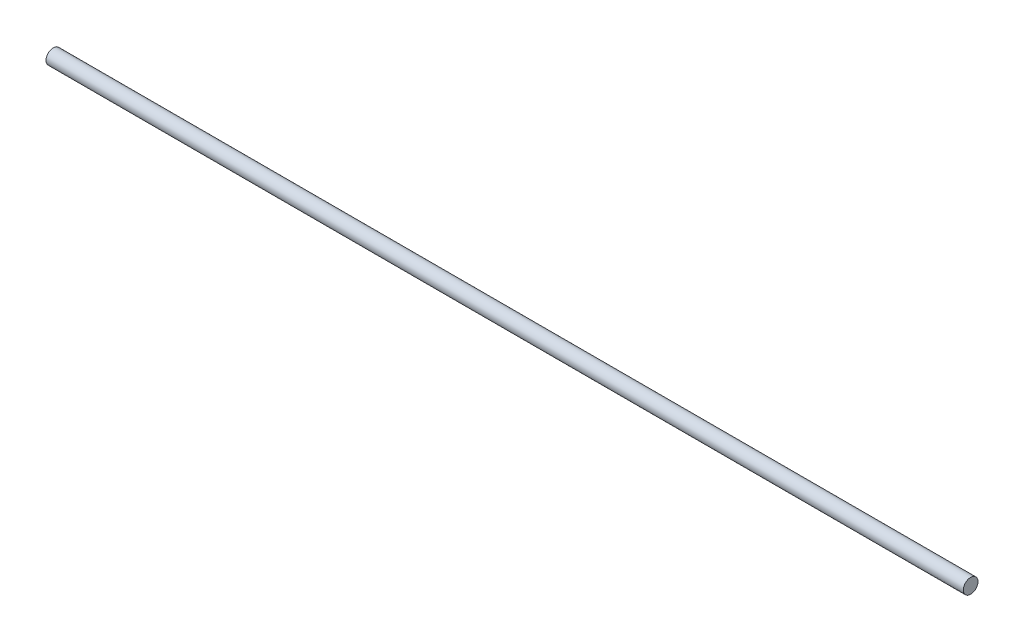
SolidWorks part; units mm, degrees
material "1023 Carbon Steel Sheet (SS)"
ref_plane "Front Plane" through (0, 0, 0) normal (0, 0, 1) x (1, 0, 0)
ref_plane "Top Plane" through (0, 0, 0) normal (0, 1, 0) x (1, 0, 0)
ref_plane "Right Plane" through (0, 0, 0) normal (1, 0, 0) x (0, 0, -1)
sketch "Sketch1" plane through (0, 0, 0) normal (1, 0, 0) x (0, 0, -1)
  circle A0 centre (0, 0) radius 6
  dimension "D1" = 12
extrude "Boss-Extrude1" add sketch "Sketch1" along normal blind 750
cosmetic thread "Cosmetic Thread1" parameters "D1"=750, "D2"=9.853
sketch "Sketch2" plane through (0, 0, 0) normal (0, 0, 1) x (1, 0, 0)
  line L0 (749.135, 6) -> (750.865, 6)
  line L1 (750.865, 6) -> (750, 4.9265)
  line L2 (750, -6) -> (750, 6) construction
  line L3 (750, 4.9265) -> (750, 6) construction
  line L4 (749.135, 6) -> (750, 4.9265)
  line L5 (750, 4.9265) -> (750, 0) construction
  dimension "D1" = 0.865
  dimension "D2" = 4.9265
sketch "Sketch4" plane through (750, 0, 0) normal (1, 0, 0) x (0, 0, -1)
  circle A0 centre (0, 0) radius 6
curve "Helix/Spiral1" pitch 1.75 height 750 turns 428.5714
equation "\"D1@Sketch2\"= \"ThreadPitch\" / 2 - 0.01 'Need to take off a fraction extra so the helix cut works"
equation "\"ThreadPitch\"= 1.75'M12 thread pitch"
equation "\"MinorThreadDiameter\"= 9.853'M12 minor thread diameter"
equation "\"D2@Sketch2\"=\"MinorThreadDiameter\"/2"
